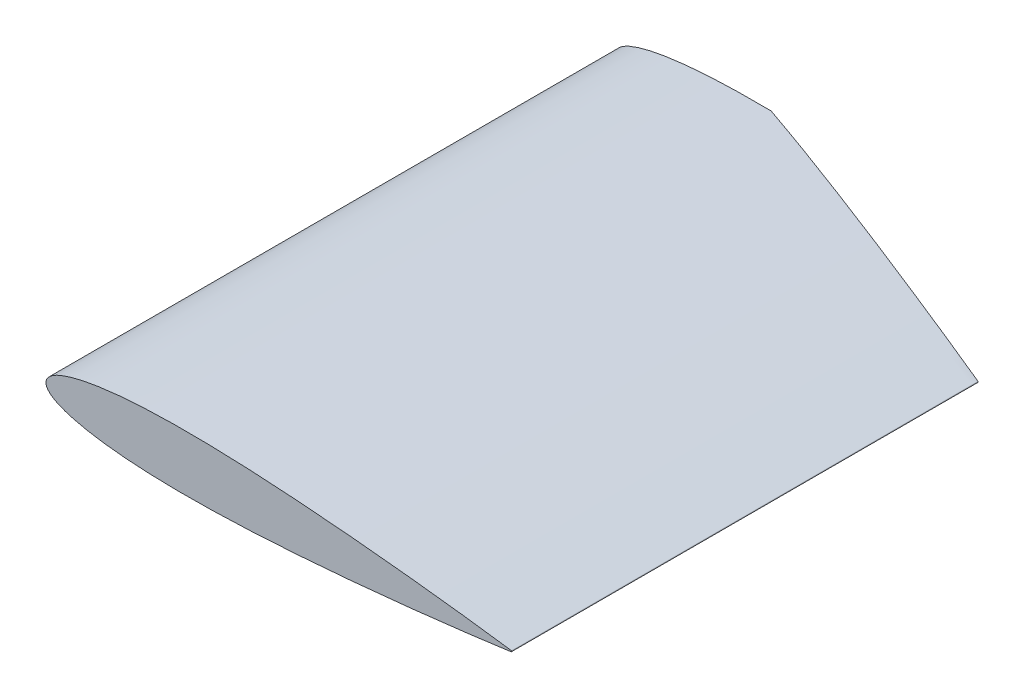
SolidWorks part; units mm, degrees
ref_plane "Front Plane" through (0, 0, 0) normal (0, 0, 1) x (1, 0, 0)
ref_plane "Top Plane" through (0, 0, 0) normal (0, 1, 0) x (1, 0, 0)
ref_plane "Right Plane" through (0, 0, 0) normal (1, 0, 0) x (0, 0, -1)
curve "Curve1"
  spline degree 3 poles (0.0004, -0.0044, 0) (-0.0002, 0, 0) (0.0004, 0.0044, 0) (0.0023, 0.0087, 0) (0.0053, 0.0128, 0) (0.0094, 0.0167, 0) (0.0147, 0.0206, 0) (0.0211, 0.0243, 0) (0.0286, 0.0279, 0) (0.0372, 0.0313, 0) (0.0468, 0.0347, 0) (0.0576, 0.0378, 0) (0.0693, 0.0408, 0) (0.0821, 0.0436, 0) (0.0958, 0.0462, 0) (0.1104, 0.0486, 0) (0.126, 0.0507, 0) (0.1425, 0.0527, 0) (0.1597, 0.0544, 0) (0.1778, 0.056, 0) (0.1966, 0.0572, 0) (0.2162, 0.0583, 0) (0.2364, 0.0591, 0) (0.2572, 0.0596, 0) (0.2786, 0.06, 0) (0.3005, 0.0601, 0) (0.3228, 0.0599, 0) (0.3456, 0.0596, 0) (0.3688, 0.0591, 0) (0.3922, 0.0583, 0) (0.4159, 0.0574, 0) (0.4398, 0.0563, 0) (0.4638, 0.0551, 0) (0.4879, 0.0537, 0) (0.5121, 0.0522, 0) (0.5362, 0.0505, 0) (0.5602, 0.0488, 0) (0.5841, 0.0469, 0) (0.6078, 0.045, 0) (0.6313, 0.043, 0) (0.6544, 0.0409, 0) (0.6772, 0.0388, 0) (0.6995, 0.0367, 0) (0.7214, 0.0345, 0) (0.7428, 0.0324, 0) (0.7636, 0.0302, 0) (0.7838, 0.028, 0) (0.8033, 0.0259, 0) (0.8222, 0.0238, 0) (0.8402, 0.0217, 0) (0.8575, 0.0196, 0) (0.874, 0.0177, 0) (0.8895, 0.0158, 0) (0.9042, 0.014, 0) (0.9179, 0.0122, 0) (0.9307, 0.0106, 0) (0.9424, 0.0091, 0) (0.9531, 0.0077, 0) (0.9627, 0.0064, 0) (0.9713, 0.0052, 0) (0.9788, 0.0042, 0) (0.9851, 0.0033, 0) (0.9903, 0.0026, 0) (0.9944, 0.002, 0) (0.9973, 0.0017, 0) (0.999, 0.0013, 0) (1.0007, 0.0014, 0) (1.0007, -0.0014, 0) (0.999, -0.0013, 0) (0.9973, -0.0017, 0) (0.9944, -0.002, 0) (0.9903, -0.0026, 0) (0.9851, -0.0033, 0) (0.9788, -0.0042, 0) (0.9713, -0.0052, 0) (0.9627, -0.0064, 0) (0.9531, -0.0077, 0) (0.9424, -0.0091, 0) (0.9307, -0.0106, 0) (0.9179, -0.0122, 0) (0.9042, -0.014, 0) (0.8895, -0.0158, 0) (0.874, -0.0177, 0) (0.8575, -0.0196, 0) (0.8402, -0.0217, 0) (0.8222, -0.0238, 0) (0.8033, -0.0259, 0) (0.7838, -0.028, 0) (0.7636, -0.0302, 0) (0.7428, -0.0324, 0) (0.7214, -0.0345, 0) (0.6995, -0.0367, 0) (0.6772, -0.0388, 0) (0.6544, -0.0409, 0) (0.6313, -0.043, 0) (0.6078, -0.045, 0) (0.5841, -0.0469, 0) (0.5602, -0.0488, 0) (0.5362, -0.0505, 0) (0.5121, -0.0522, 0) (0.4879, -0.0537, 0) (0.4638, -0.0551, 0) (0.4398, -0.0563, 0) (0.4159, -0.0574, 0) (0.3922, -0.0583, 0) (0.3688, -0.0591, 0) (0.3456, -0.0596, 0) (0.3228, -0.0599, 0) (0.3005, -0.0601, 0) (0.2786, -0.06, 0) (0.2572, -0.0596, 0) (0.2364, -0.0591, 0) (0.2162, -0.0583, 0) (0.1966, -0.0572, 0) (0.1778, -0.056, 0) (0.1597, -0.0544, 0) (0.1425, -0.0527, 0) (0.126, -0.0507, 0) (0.1104, -0.0486, 0) (0.0958, -0.0462, 0) (0.0821, -0.0436, 0) (0.0693, -0.0408, 0) (0.0576, -0.0378, 0) (0.0468, -0.0347, 0) (0.0372, -0.0313, 0) (0.0286, -0.0279, 0) (0.0211, -0.0243, 0) (0.0147, -0.0206, 0) (0.0094, -0.0167, 0) (0.0053, -0.0128, 0) (0.0023, -0.0087, 0) (0.0004, -0.0044, 0) (-0.0002, 0, 0) (0.0004, 0.0044, 0) knots -0.006773 -0.004321 -0.002106 0 0.002106 0.004321 0.006773 0.009557 0.012734 0.016343 0.020406 0.024934 0.029933 0.035402 0.041337 0.047732 0.054575 0.061857 0.069565 0.077682 0.086195 0.095084 0.104333 0.113922 0.123829 0.134035 0.144516 0.155249 0.16621 0.177376 0.18872 0.200217 0.21184 0.223563 0.235359 0.2472 0.259058 0.270907 0.282718 0.294465 0.306118 0.317651 0.329037 0.340249 0.35126 0.362045 0.372579 0.382836 0.392793 0.402425 0.411711 0.420628 0.429156 0.437273 0.444962 0.452203 0.458979 0.465275 0.471075 0.476366 0.481134 0.485369 0.48906 0.492198 0.494776 0.496788 0.498228 0.499094 0.499383 0.500617 0.500906 0.501772 0.503212 0.505224 0.507802 0.51094 0.514631 0.518866 0.523634 0.528925 0.534725 0.541021 0.547797 0.555038 0.562727 0.570844 0.579372 0.588289 0.597575 0.607207 0.617164 0.627421 0.637955 0.64874 0.659751 0.670963 0.682349 0.693882 0.705535 0.717282 0.729093 0.740942 0.7528 0.764641 0.776437 0.78816 0.799783 0.81128 0.822624 0.83379 0.844751 0.855484 0.865965 0.876171 0.886078 0.895667 0.904916 0.913805 0.922318 0.930435 0.938143 0.945425 0.952268 0.958663 0.964598 0.970067 0.975066 0.979594 0.983657 0.987266 0.990443 0.993227 0.995679 0.997894 1 1.002106 1.004321 1.006773 periodic
sketch "Sketch1" plane through (0, 0, 0) normal (0, 0, 1) x (1, 0, 0)
  line L0 (228.6, 0) -> (0, 0) construction
  line L1 (0.5505, 0) -> (-0.5505, 0) construction
  line L2 (0, 0) -> (0, 0.0037) construction
  line L3 (0, -0.0661) -> (0, 0.0661) construction
  spline S1 degree 3 poles (0.0941, 1.0023) (-0.0459, 0) (0.0941, -1.0023) (0.5163, -1.979) (1.2063, -2.9191) (2.1555, -3.8265) (3.3611, -4.7045) (4.8212, -5.5539) (6.5336, -6.3738) (8.4955, -7.1622) (10.7028, -7.9169) (13.1508, -8.6353) (15.8342, -9.3147) (18.7469, -9.9527) (21.8822, -10.5465) (25.2329, -11.0942) (28.7913, -11.5933) (32.549, -12.0423) (36.4974, -12.4394) (40.6273, -12.7838) (44.929, -13.0744) (49.3924, -13.3108) (54.0073, -13.4932) (58.7627, -13.6218) (63.6477, -13.6973) (68.6508, -13.7209) (73.7603, -13.694) (78.9643, -13.6184) (84.2506, -13.4961) (89.607, -13.3294) (95.0208, -13.1208) (100.4795, -12.873) (105.9703, -12.5887) (111.4804, -12.2709) (116.997, -11.9225) (122.507, -11.5464) (127.9978, -11.1457) (133.4564, -10.7232) (138.8702, -10.2819) (144.2264, -9.8246) (149.5125, -9.354) (154.7163, -8.873) (159.8255, -8.3842) (164.8283, -7.89) (169.7129, -7.3931) (174.468, -6.8959) (179.0824, -6.4008) (183.5453, -5.9102) (187.8464, -5.4263) (191.9755, -4.9516) (195.9231, -4.4883) (199.6799, -4.0386) (203.2372, -3.6048) (206.5865, -3.1892) (209.7203, -2.7938) (212.631, -2.4208) (215.3118, -2.0722) (217.7567, -1.7502) (219.9598, -1.4564) (221.9158, -1.1925) (223.6207, -0.9608) (225.0694, -0.7609) (226.261, -0.599) (227.1864, -0.4629) (227.8589, -0.3857) (228.2452, -0.3022) (228.6415, -0.3098) (228.6415, 0.3098) (228.2452, 0.3022) (227.8589, 0.3857) (227.1864, 0.4629) (226.261, 0.599) (225.0694, 0.7609) (223.6207, 0.9608) (221.9158, 1.1925) (219.9598, 1.4564) (217.7567, 1.7502) (215.3118, 2.0722) (212.631, 2.4208) (209.7203, 2.7938) (206.5865, 3.1892) (203.2372, 3.6048) (199.6799, 4.0386) (195.9231, 4.4883) (191.9755, 4.9516) (187.8464, 5.4263) (183.5453, 5.9102) (179.0824, 6.4008) (174.468, 6.8959) (169.7129, 7.3931) (164.8283, 7.89) (159.8255, 8.3842) (154.7163, 8.873) (149.5125, 9.354) (144.2264, 9.8246) (138.8702, 10.2819) (133.4564, 10.7232) (127.9978, 11.1457) (122.507, 11.5464) (116.997, 11.9225) (111.4804, 12.2709) (105.9703, 12.5887) (100.4795, 12.873) (95.0208, 13.1208) (89.607, 13.3294) (84.2506, 13.4961) (78.9643, 13.6184) (73.7603, 13.694) (68.6508, 13.7209) (63.6477, 13.6973) (58.7627, 13.6218) (54.0073, 13.4932) (49.3924, 13.3108) (44.929, 13.0744) (40.6273, 12.7838) (36.4974, 12.4394) (32.549, 12.0423) (28.7913, 11.5933) (25.2329, 11.0942) (21.8822, 10.5465) (18.7469, 9.9527) (15.8342, 9.3147) (13.1508, 8.6353) (10.7028, 7.9169) (8.4955, 7.1622) (6.5336, 6.3738) (4.8212, 5.5539) (3.3611, 4.7045) (2.1555, 3.8265) (1.2063, 2.9191) (0.5163, 1.979) (0.0941, 1.0023) (-0.0459, 0) (0.0941, -1.0023) knots -0.006773 -0.004321 -0.002106 0 0.002106 0.004321 0.006773 0.009557 0.012734 0.016343 0.020406 0.024934 0.029933 0.035402 0.041337 0.047732 0.054575 0.061857 0.069565 0.077682 0.086195 0.095084 0.104333 0.113922 0.123829 0.134035 0.144516 0.155249 0.16621 0.177376 0.18872 0.200217 0.21184 0.223563 0.235359 0.2472 0.259058 0.270907 0.282718 0.294465 0.306118 0.317651 0.329037 0.340249 0.35126 0.362045 0.372579 0.382836 0.392793 0.402425 0.411711 0.420628 0.429156 0.437273 0.444962 0.452203 0.458979 0.465275 0.471075 0.476366 0.481134 0.485369 0.48906 0.492198 0.494776 0.496788 0.498228 0.499094 0.499383 0.500617 0.500906 0.501772 0.503212 0.505224 0.507802 0.51094 0.514631 0.518866 0.523634 0.528925 0.534725 0.541021 0.547797 0.555038 0.562727 0.570844 0.579372 0.588289 0.597575 0.607207 0.617164 0.627421 0.637955 0.64874 0.659751 0.670963 0.682349 0.693882 0.705535 0.717282 0.729093 0.740942 0.7528 0.764641 0.776437 0.78816 0.799783 0.81128 0.822624 0.83379 0.844751 0.855484 0.865965 0.876171 0.886078 0.895667 0.904916 0.913805 0.922318 0.930435 0.938143 0.945425 0.952268 0.958663 0.964598 0.970067 0.975066 0.979594 0.983657 0.987266 0.990443 0.993227 0.995679 0.997894 1 1.002106 1.004321 1.006773 only from (0, 0) to (0, 0)
  dimension "D1" = 228.6
extrude "Boss-Extrude1" add sketch "Sketch1" along normal blind 279.908
sketch "Sketch2" plane through (0, 0, 0) normal (0, 0, -1) x (-1, 0, 0)
  line L0 (125.7781, 0) -> (-125.7781, 0) construction
  circle A0 centre (-63.5, 0) radius 6.35
  point P4 (0, 0)
  dimension "D1" = 12.7
  dimension "D2" = 63.5
extrude "Cut-Extrude1" cut sketch "Sketch2" against normal blind 127
sketch "Sketch3" plane through (0, 0, 0) normal (0, 1, 0) x (1, 0, 0)
  line L0 (228.655, 0) -> (228.6, -50.8)
  line L1 (-15.093, 0) -> (15.093, 0) construction
  line L2 (228.6, -279.908) -> (228.6, 0) construction
  line L3 (228.6, -50.8) -> (76.2, 0)
  line L4 (76.2, 0) -> (228.655, 0)
  dimension "D1" = 152.4
  dimension "D2" = 50.8
extrude "Cut-Extrude2" cut sketch "Sketch3" against normal up to next and the other way up to next
